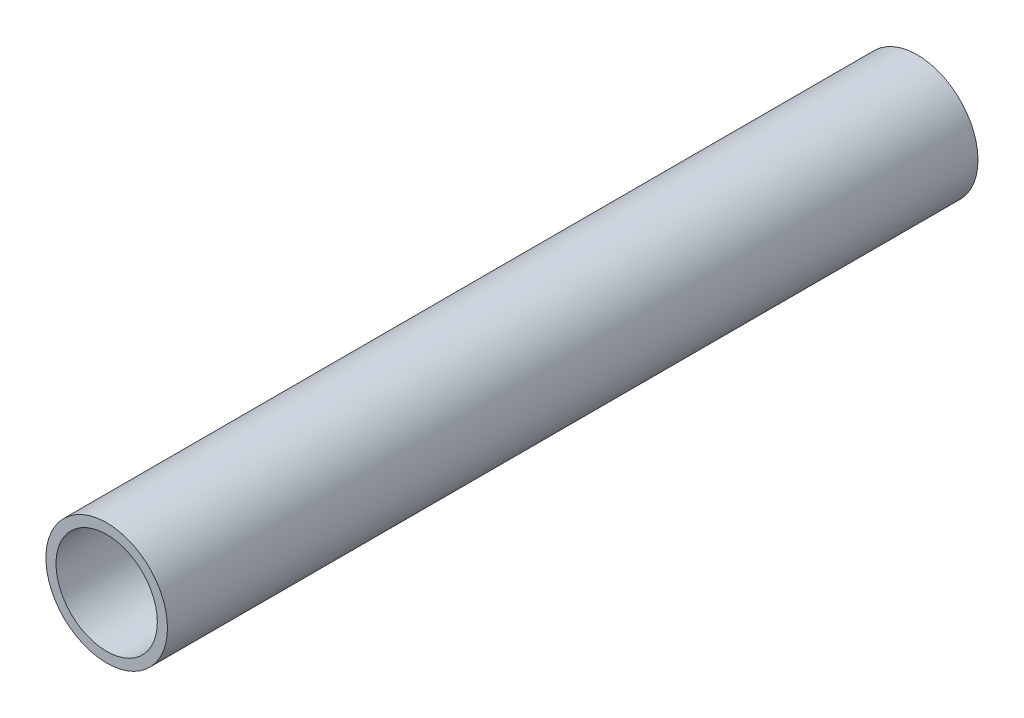
SolidWorks part; units mm, degrees
material "AISI 316 Annealed Stainless Steel Bar (SS)"
ref_plane "Front Plane" through (0, 0, 0) normal (0, 0, 1) x (1, 0, 0)
ref_plane "Top Plane" through (0, 0, 0) normal (0, 1, 0) x (1, 0, 0)
ref_plane "Right Plane" through (0, 0, 0) normal (1, 0, 0) x (0, 0, -1)
sketch "Sketch1" plane through (0, 0, 0) normal (0, 0, 1) x (1, 0, 0)
  circle A0 centre (0, 0) radius 6
  circle A1 centre (0, 0) radius 5
  dimension "D1" = 12
  dimension "D2" = 10
extrude "Boss-Extrude1" add sketch "Sketch1" along normal blind 80
